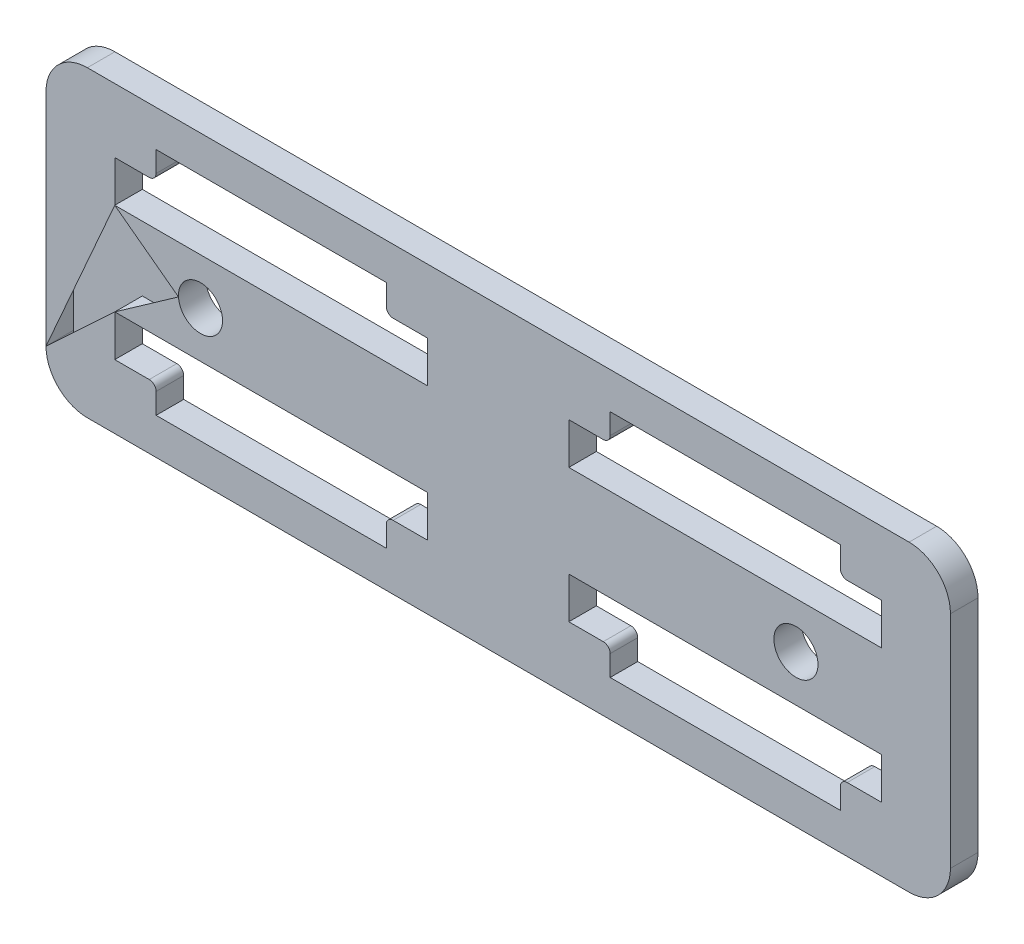
SolidWorks part; units mm, degrees
ref_plane "前视基准面" through (0, 0, 0) normal (0, 0, 1) x (1, 0, 0)
ref_plane "上视基准面" through (0, 0, 0) normal (0, 1, 0) x (1, 0, 0)
ref_plane "右视基准面" through (0, 0, 0) normal (1, 0, 0) x (0, 0, -1)
sketch "草图1" plane through (0, 0, 0) normal (0, 0, 1) x (1, 0, 0)
  line L0 (-29.8125, 11) -> (29.8125, 11)
  line L1 (32.8125, 8) -> (32.8125, -8)
  line L2 (29.8125, -11) -> (-29.8125, -11)
  line L3 (-24.823, 6.85) -> (-24.823, 8.35) construction
  line L4 (-27.823, -6.35) -> (-25.323, -6.35)
  line L5 (-27.823, -3.35) -> (-27.823, -6.35)
  line L6 (-5.123, -3.35) -> (-27.823, -3.35)
  line L7 (-5.123, -6.35) -> (-5.123, -3.35)
  line L8 (-7.623, -6.35) -> (-5.123, -6.35)
  line L9 (-8.123, -8.35) -> (-8.123, -6.85)
  line L10 (-24.823, -8.35) -> (-8.123, -8.35)
  line L11 (-24.823, -6.85) -> (-24.823, -8.35)
  line L12 (-8.123, 8.35) -> (-24.823, 8.35)
  line L13 (-8.123, 6.85) -> (-8.123, 8.35)
  line L14 (-5.123, 6.35) -> (-7.623, 6.35)
  line L15 (-5.123, 3.35) -> (-5.123, 6.35)
  line L16 (-27.823, 3.35) -> (-5.123, 3.35)
  line L17 (-27.823, 6.35) -> (-27.823, 3.35)
  line L18 (-25.323, 6.35) -> (-27.823, 6.35)
  line L19 (0, 11) -> (0, -11) construction
  line L20 (-32.8125, 8) -> (-32.8125, -8)
  line L21 (-24.823, 8.35) -> (-24.823, 6.85)
  line L37 (24.823, 6.85) -> (24.823, 8.35) construction
  line L38 (24.823, 8.35) -> (24.823, 6.85)
  line L39 (25.323, 6.35) -> (27.823, 6.35)
  line L40 (27.823, 6.35) -> (27.823, 3.35)
  line L41 (27.823, 3.35) -> (5.123, 3.35)
  line L42 (5.123, 3.35) -> (5.123, 6.35)
  line L43 (5.123, 6.35) -> (7.623, 6.35)
  line L44 (8.123, 6.85) -> (8.123, 8.35)
  line L45 (8.123, 8.35) -> (24.823, 8.35)
  line L46 (24.823, -6.85) -> (24.823, -8.35)
  line L47 (24.823, -8.35) -> (8.123, -8.35)
  line L48 (8.123, -8.35) -> (8.123, -6.85)
  line L49 (7.623, -6.35) -> (5.123, -6.35)
  line L50 (5.123, -6.35) -> (5.123, -3.35)
  line L51 (5.123, -3.35) -> (27.823, -3.35)
  line L52 (27.823, -3.35) -> (27.823, -6.35)
  line L53 (27.823, -6.35) -> (25.323, -6.35)
  circle A0 centre (-21.603, 0) radius 1.6
  arc A1 (-7.623, -6.35) -> (-8.123, -6.85) centre (-7.623, -6.85) ccw
  arc A2 (-24.823, -6.85) -> (-25.323, -6.35) centre (-25.323, -6.85) ccw
  arc A3 (-8.123, 6.85) -> (-7.623, 6.35) centre (-7.623, 6.85) ccw
  arc A4 (-25.323, 6.35) -> (-24.823, 6.85) centre (-25.323, 6.85) ccw
  arc A20 (32.8125, -8) -> (29.8125, -11) centre (29.8125, -8) cw
  arc A21 (-32.8125, -8) -> (-29.8125, -11) centre (-29.8125, -8) ccw
  arc A22 (29.8125, 11) -> (32.8125, 8) centre (29.8125, 8) cw
  arc A23 (-32.8125, 8) -> (-29.8125, 11) centre (-29.8125, 8) cw
  arc A24 (25.323, 6.35) -> (24.823, 6.85) centre (25.323, 6.85) cw
  arc A25 (8.123, 6.85) -> (7.623, 6.35) centre (7.623, 6.85) cw
  arc A26 (24.823, -6.85) -> (25.323, -6.35) centre (25.323, -6.85) cw
  arc A27 (7.623, -6.35) -> (8.123, -6.85) centre (7.623, -6.85) cw
  circle A28 centre (21.603, 0) radius 1.6
  point P81 (32.8125, -11)
  point P84 (-32.8125, -11)
  point P87 (32.8125, 11)
  point P90 (-32.8125, 11)
  dimension "D2" = 3
extrude "凸台-拉伸1" add sketch "草图1" along normal blind 2
